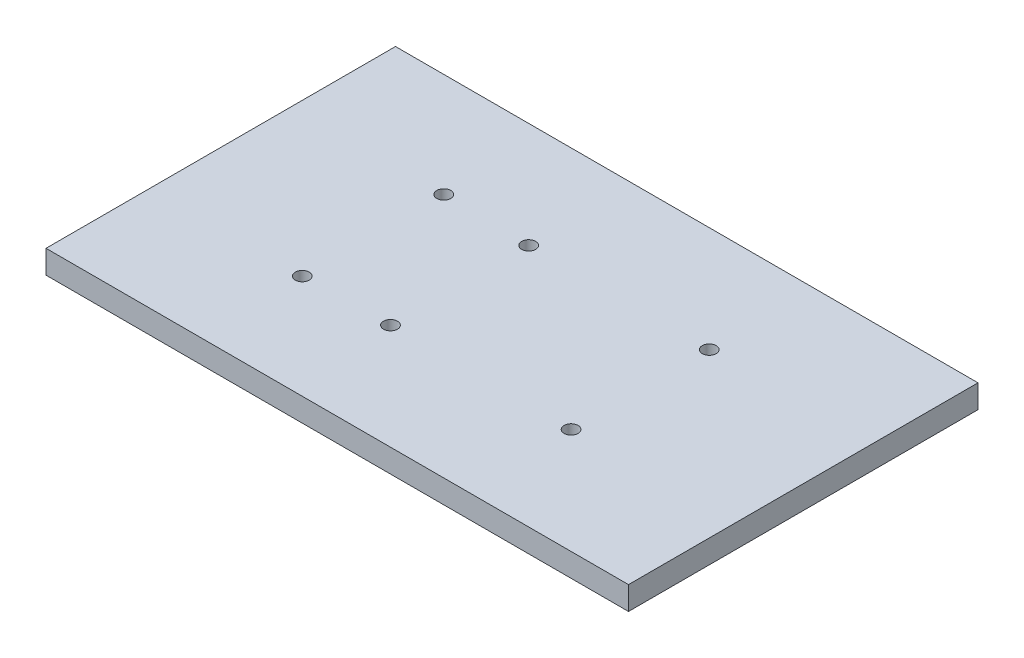
SolidWorks part; units mm, degrees
ref_plane "Front Plane" through (0, 0, 0) normal (0, 0, 1) x (1, 0, 0)
ref_plane "Top Plane" through (0, 0, 0) normal (0, 1, 0) x (1, 0, 0)
ref_plane "Right Plane" through (0, 0, 0) normal (1, 0, 0) x (0, 0, -1)
sketch "Sketch1" plane through (0, 0, 0) normal (0, 1, 0) x (1, 0, 0)
  line L0 (1120.4598, 0) -> (63.5, 0) construction
  line L1 (-63.5, -38.1) -> (63.5, -38.1)
  line L2 (-63.5, -38.1) -> (-63.5, 38.1)
  line L3 (-63.5, 38.1) -> (63.5, 38.1)
  line L4 (63.5, -38.1) -> (63.5, 38.1)
  line L5 (0, 0) -> (23.8505, 14.3103) construction
  line L6 (0, 0) -> (23.8505, -14.3103) construction
  line L7 (26.4639, 15.8783) -> (63.5, 38.1) construction
  line L8 (0, 0) -> (-73.5989, 0) construction
  line L9 (26.4639, -15.8783) -> (63.5, -38.1) construction
  point P0 (0, 0)
  point P20 (0, 0)
  dimension "D1" = 127
  dimension "D2" = 76.2
extrude "Boss-Extrude1" add sketch "Sketch1" along normal blind 5.08 contours L2 L1 L4 L3
sketch "Sketch3" plane through (0, 5.08, 0) normal (0, 1, 0) x (1, 0, 0)
  line L0 (10.795, 0) -> (-54.0168, 0) construction
  line L4 (63.5, 38.1) -> (-63.5, 38.1)
  line L5 (-63.5, 38.1) -> (-63.5, -38.1)
  line L6 (-63.5, -38.1) -> (63.5, -38.1)
  line L7 (63.5, -38.1) -> (63.5, 38.1)
  line L8 (63.5, 38.1) -> (-63.5, 38.1)
  line L9 (-63.5, 38.1) -> (-63.5, -38.1)
  line L10 (-63.5, -38.1) -> (63.5, -38.1)
  line L11 (63.5, -38.1) -> (63.5, 38.1)
  line L14 (-9.8609, 17.78) -> (-12.9991, 17.78)
  line L15 (-12.9991, 17.78) -> (-14.5682, 15.0622)
  line L16 (-14.5682, 15.0622) -> (-12.9991, 12.3444)
  line L17 (-12.9991, 12.3444) -> (-9.8609, 12.3444)
  line L18 (-9.8609, 12.3444) -> (-8.2918, 15.0622)
  line L19 (-8.2918, 15.0622) -> (-9.8609, 17.78)
  line L20 (-9.8609, 17.78) -> (-12.9991, 17.78)
  line L21 (-12.9991, 17.78) -> (-14.5682, 15.0622)
  line L22 (-14.5682, 15.0622) -> (-12.9991, 12.3444)
  line L23 (-12.9991, 12.3444) -> (-9.8609, 12.3444)
  line L24 (-9.8609, 12.3444) -> (-8.2918, 15.0622)
  line L25 (-8.2918, 15.0622) -> (-9.8609, 17.78)
  line L26 (31.0782, -15.0622) -> (29.5091, -12.3444)
  line L27 (29.5091, -12.3444) -> (26.3709, -12.3444)
  line L28 (26.3709, -12.3444) -> (24.8018, -15.0622)
  line L29 (24.8018, -15.0622) -> (26.3709, -17.78)
  line L30 (26.3709, -17.78) -> (29.5091, -17.78)
  line L31 (29.5091, -17.78) -> (31.0782, -15.0622)
  line L32 (31.0782, -15.0622) -> (29.5091, -12.3444)
  line L33 (29.5091, -12.3444) -> (26.3709, -12.3444)
  line L34 (26.3709, -12.3444) -> (24.8018, -15.0622)
  line L35 (24.8018, -15.0622) -> (26.3709, -17.78)
  line L36 (26.3709, -17.78) -> (29.5091, -17.78)
  line L37 (29.5091, -17.78) -> (31.0782, -15.0622)
  line L38 (26.3709, 17.78) -> (24.8018, 15.0622)
  line L39 (29.5091, 17.78) -> (26.3709, 17.78)
  line L40 (31.0782, 15.0622) -> (29.5091, 17.78)
  line L41 (29.5091, 12.3444) -> (31.0782, 15.0622)
  line L42 (26.3709, 12.3444) -> (29.5091, 12.3444)
  line L43 (24.8018, 15.0622) -> (26.3709, 12.3444)
  line L44 (26.3709, 17.78) -> (24.8018, 15.0622)
  line L45 (29.5091, 17.78) -> (26.3709, 17.78)
  line L46 (31.0782, 15.0622) -> (29.5091, 17.78)
  line L47 (29.5091, 12.3444) -> (31.0782, 15.0622)
  line L48 (26.3709, 12.3444) -> (29.5091, 12.3444)
  line L49 (24.8018, 15.0622) -> (26.3709, 12.3444)
  line L50 (-9.8609, -17.78) -> (-8.2918, -15.0622)
  line L51 (-12.9991, -17.78) -> (-9.8609, -17.78)
  line L52 (-14.5682, -15.0622) -> (-12.9991, -17.78)
  line L53 (-12.9991, -12.3444) -> (-14.5682, -15.0622)
  line L54 (-9.8609, -12.3444) -> (-12.9991, -12.3444)
  line L55 (-8.2918, -15.0622) -> (-9.8609, -12.3444)
  line L56 (-9.8609, -17.78) -> (-8.2918, -15.0622)
  line L57 (-12.9991, -17.78) -> (-9.8609, -17.78)
  line L58 (-14.5682, -15.0622) -> (-12.9991, -17.78)
  line L59 (-12.9991, -12.3444) -> (-14.5682, -15.0622)
  line L60 (-9.8609, -12.3444) -> (-12.9991, -12.3444)
  line L61 (-8.2918, -15.0622) -> (-9.8609, -12.3444)
  line L62 (-27.5844, 15.4263) -> (-28.9433, 17.78)
  line L63 (-28.9433, 17.78) -> (-31.6611, 17.78)
  line L64 (-31.6611, 17.78) -> (-33.02, 15.4263)
  line L65 (-33.02, 15.4263) -> (-31.6611, 13.0726)
  line L66 (-31.6611, 13.0726) -> (-28.9433, 13.0726)
  line L67 (-28.9433, 13.0726) -> (-27.5844, 15.4263)
  line L68 (-27.5844, 15.4263) -> (-28.9433, 17.78)
  line L69 (-28.9433, 17.78) -> (-31.6611, 17.78)
  line L70 (-31.6611, 17.78) -> (-33.02, 15.4263)
  line L71 (-33.02, 15.4263) -> (-31.6611, 13.0726)
  line L72 (-31.6611, 13.0726) -> (-28.9433, 13.0726)
  line L73 (-28.9433, 13.0726) -> (-27.5844, 15.4263)
  circle A0 centre (-30.3022, -15.4263) radius 1.524
  circle A1 centre (27.94, -15.0622) radius 1.524
  circle A2 centre (27.94, -15.0622) radius 1.524
  circle A3 centre (-11.43, -15.0622) radius 1.524
  circle A4 centre (-11.43, -15.0622) radius 1.524
  circle A5 centre (27.94, 15.0622) radius 1.524
  circle A6 centre (27.94, 15.0622) radius 1.524
  circle A7 centre (-11.43, 15.0622) radius 1.524
  circle A8 centre (-11.43, 15.0622) radius 1.524
  circle A9 centre (-30.3022, 15.4263) radius 1.524
  circle A10 centre (-30.3022, 15.4263) radius 1.524
  dimension "D1" = 0
  dimension "D2" = 0
  dimension "D3" = 0
  dimension "D4" = 0
  dimension "D5" = 0
  dimension "D6" = 0
  dimension "D7" = 0
  dimension "D8" = 0
  dimension "D9" = 0
  dimension "D10" = 0
  dimension "D11" = 0
extrude "Cut-Extrude3" cut sketch "Sketch3" against normal through all contours A6 | A2 | A8 | A4 | A0 | A10
chamfer "Chamfer1" distance 0.254 angle 45 6 edges at (-30.3022, 0, 13.9023) (-30.3022, 0, -13.9023) (-11.43, 0, -13.5382) (-11.43, 0, 16.5862) (27.94, 0, 16.5862) (27.94, 0, -13.5382)
